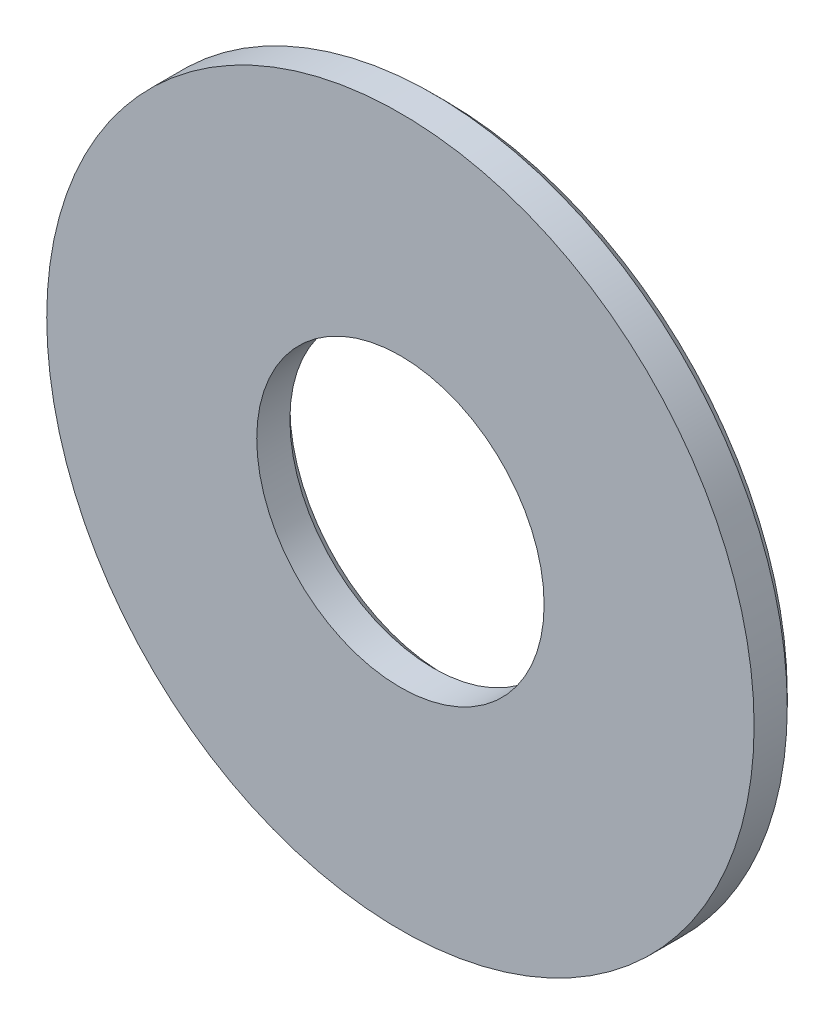
SolidWorks part; units mm, degrees
ref_plane "Front Plane" through (0, 0, 0) normal (0, 0, 1) x (1, 0, 0)
ref_plane "Top Plane" through (0, 0, 0) normal (0, 1, 0) x (1, 0, 0)
ref_plane "Right Plane" through (0, 0, 0) normal (1, 0, 0) x (0, 0, -1)
sketch "Sketch1" plane through (0, 0, 0) normal (0, 0, 1) x (1, 0, 0)
  circle A0 centre (0, 0) radius 3.25
  circle A1 centre (0, 0) radius 8
  dimension "D1" = 6.5
  dimension "D2" = 16
extrude "Boss-Extrude1" add sketch "Sketch1" along normal blind 1
chamfer "Chamfer1" distance 0.25 angle 45 2 edges at (3.25, 0, 0) (8, 0, 0)
